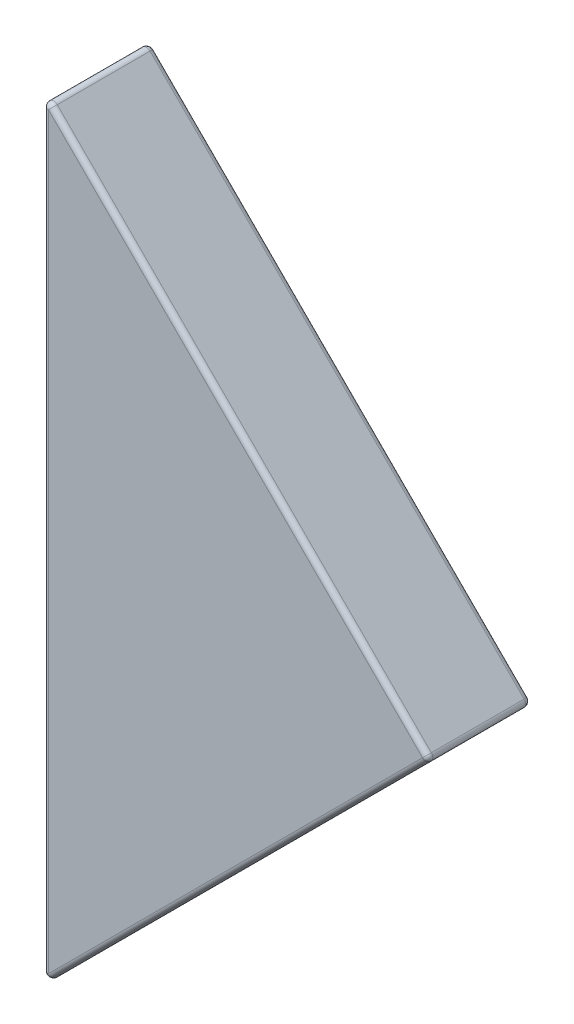
SolidWorks part; units mm, degrees
ref_plane "前视基准面" through (0, 0, 0) normal (0, 0, 1) x (1, 0, 0)
ref_plane "上视基准面" through (0, 0, 0) normal (0, 1, 0) x (1, 0, 0)
ref_plane "右视基准面" through (0, 0, 0) normal (1, 0, 0) x (0, 0, -1)
sketch "草图1" plane through (0, 0, 0) normal (0, 0, 1) x (1, 0, 0)
  line L13 (0, 75) -> (37.5, 37.5)
  line L15 (37.5, 37.5) -> (0, 0)
  line L16 (0, 0) -> (0, 75)
  dimension "D5" = 45
  dimension "D4" = 45
  dimension "D3" = 75
extrude "凸台-拉伸1" add sketch "草图1" along normal blind 10
fillet "圆角1" radius 0.5 9 edges at (18.75, 56.25, 0) (0, 37.5, 10) (18.75, 18.75, 10) (18.75, 56.25, 10) (0, 75, 5) (37.5, 37.5, 5) (0, 0, 5) (18.75, 18.75, 0) (0, 37.5, 0)
